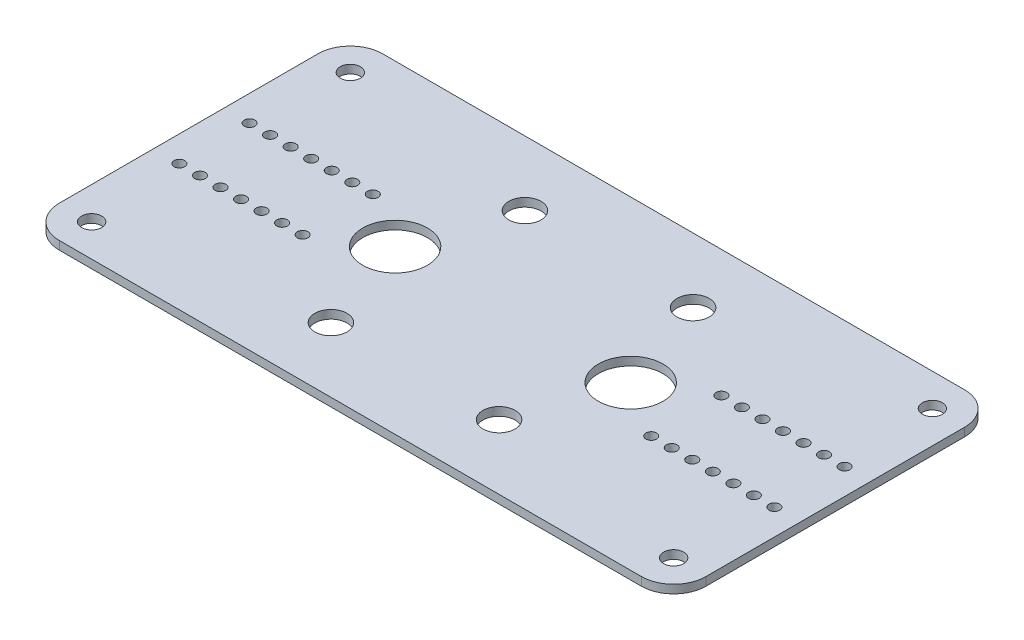
SolidWorks part; units mm, degrees
ref_plane "Front Plane" through (0, 0, 0) normal (0, 0, 1) x (1, 0, 0)
ref_plane "Top Plane" through (0, 0, 0) normal (0, 1, 0) x (1, 0, 0)
ref_plane "Right Plane" through (0, 0, 0) normal (1, 0, 0) x (0, 0, -1)
sketch "Sketch1" plane through (0, 0, 0) normal (0, 1, 0) x (1, 0, 0)
  line L1 (0, 0) -> (200, 0)
  line L2 (0, 0) -> (0, -100)
  line L3 (0, -100) -> (200, -100)
  line L4 (200, 0) -> (200, -100)
  point P4 (0, 0)
  dimension "D1" = 100
  dimension "D2" = 200
extrude "Boss-Extrude1" add sketch "Sketch1" along normal blind 2.6 contours L1 L4 L3 L2
fillet "Fillet1" radius 10 4 edges at (0, 1.3, 0) (0, 1.3, 100) (200, 1.3, 100) (200, 1.3, 0)
sketch "Sketch6" plane through (0, 0, 0) normal (0, -1, 0) x (1, 0, 0)
  line L0 (200, 10) -> (200, 90) construction
  line L1 (10, 0) -> (190, 0) construction
  circle A0 centre (190, 10) radius 3.1
  dimension "D1" = 6.2
  dimension "D2" = 10
  dimension "D3" = 10
sketch "Sketch8" plane through (0, 0, 0) normal (0, -1, 0) x (1, 0, 0)
  line L0 (200, 10) -> (200, 90) construction
  line L2 (200, 50) -> (0, 50) construction
  line L3 (0, 10) -> (0, 90) construction
  line L4 (200, 10) -> (200, 90) construction
  circle A0 centre (192, 60.85) radius 1.65
  circle A1 centre (192, 39.15) radius 1.65
  dimension "D1" = 3.3
  dimension "D2" = 10.85
  dimension "D3" = 8
  dimension "D4" = 8
  dimension "D5" = 10.85
  dimension "D6" = 3.3
extrude "Cut-Extrude4" cut sketch "Sketch8" against normal blind 2.6
pattern_linear "LPattern1" count 7 spacing 6.35 along (-1, 0, 0) of "Cut-Extrude4"
ref_plane "Plane1" through (100, 0, 0) normal (1, 0, 0) x (0, 0, -1)
mirror "Mirror1" about plane through (100, 0, 0) normal (1, 0, 0) of "Cut-Extrude4", "LPattern1"
extrude "Cut-Extrude6" cut sketch "Sketch6" against normal blind 2.6 contours A0
ref_plane "Plane14" through (0, 0, 50) normal (0, 0, 1) x (1, 0, 0)
mirror "Mirror5" about plane through (100, 0, 0) normal (1, 0, 0) of "Cut-Extrude6"
mirror "Mirror6" about plane through (0, 0, 50) normal (0, 0, 1) of "Mirror5", "Cut-Extrude6"
sketch "Sketch13" plane through (0, 2.6, 0) normal (0, 1, 0) x (1, 0, 0)
  line L0 (100, -44) -> (100, 44) construction
  line L1 (-1.43, -50) -> (1.43, -50) construction
  circle A0 centre (74, -80) radius 4.9806
  dimension "D1" = 26
  dimension "D2" = 30
extrude "Cut-Extrude7" cut sketch "Sketch13" against normal blind 2.6
mirror "Mirror7" about plane through (0, 0, 50) normal (0, 0, 1) of "Cut-Extrude7"
mirror "Mirror8" about plane through (100, 0, 0) normal (1, 0, 0) of "Cut-Extrude7", "Mirror7"
sketch "Sketch15" plane through (0, 0, 0) normal (0, -1, 0) x (1, 0, 0)
  circle A0 centre (63.5719, 49.722) radius 10
  point P2 (0, 0)
  point P3 (63.5719, 49.722)
  dimension "D1" = 20
extrude "Cut-Extrude8" cut sketch "Sketch15" against normal blind 2.6
mirror "Mirror9" about plane through (100, 0, 0) normal (1, 0, 0) of "Cut-Extrude8"
